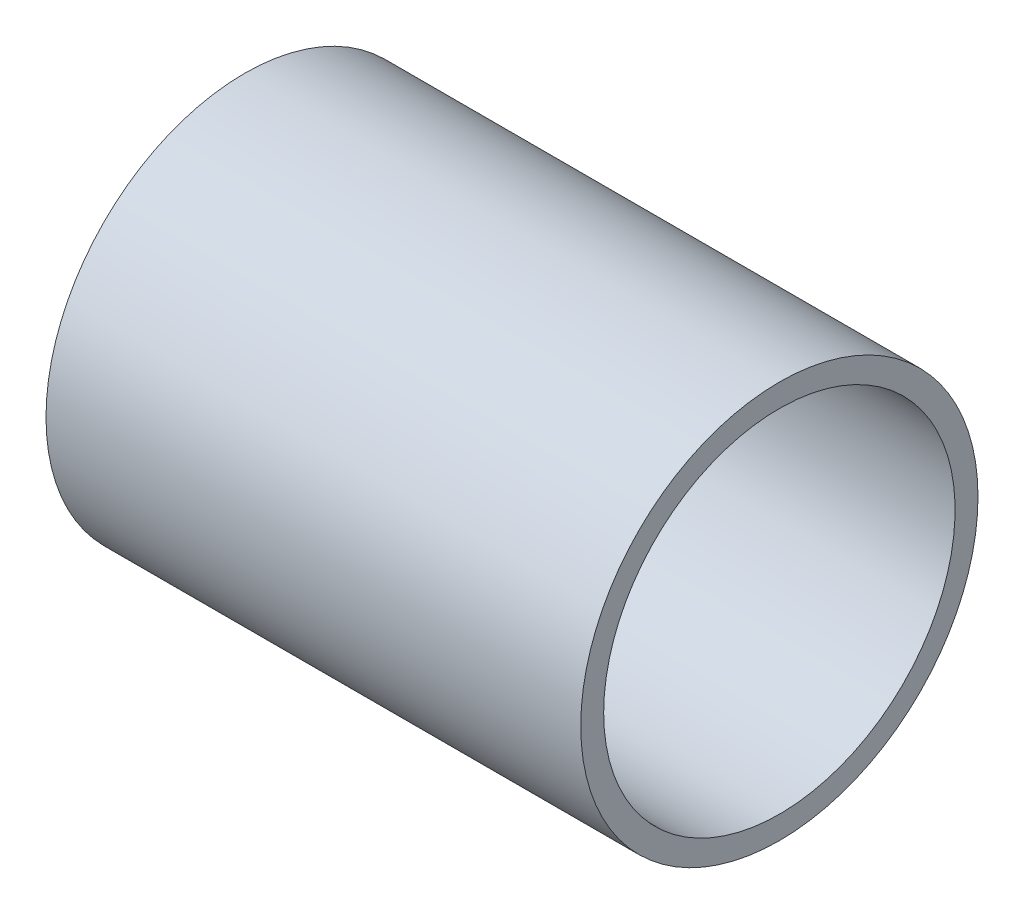
SolidWorks part; units mm, degrees
ref_plane "Front Plane" through (0, 0, 0) normal (0, 0, 1) x (1, 0, 0)
ref_plane "Top Plane" through (0, 0, 0) normal (0, 1, 0) x (1, 0, 0)
ref_plane "Right Plane" through (0, 0, 0) normal (1, 0, 0) x (0, 0, -1)
sketch "Sketch1" plane through (0, 0, 0) normal (0, 0, 1) x (1, 0, 0)
  line L0 (0, 0) -> (34672.6608, 0) construction
  line L1 (0, 0) -> (0, 34672.6608) construction
  line L2 (0, 26) -> (70, 26)
  line L3 (70, 26) -> (70, 23)
  line L4 (70, 23) -> (0, 23)
  line L5 (0, 23) -> (0, 26)
  dimension "D1" = 70
  dimension "D2" = 52
  dimension "D3" = 46
revolve "Revolve1" add sketch "Sketch1" angle 360 about L0
